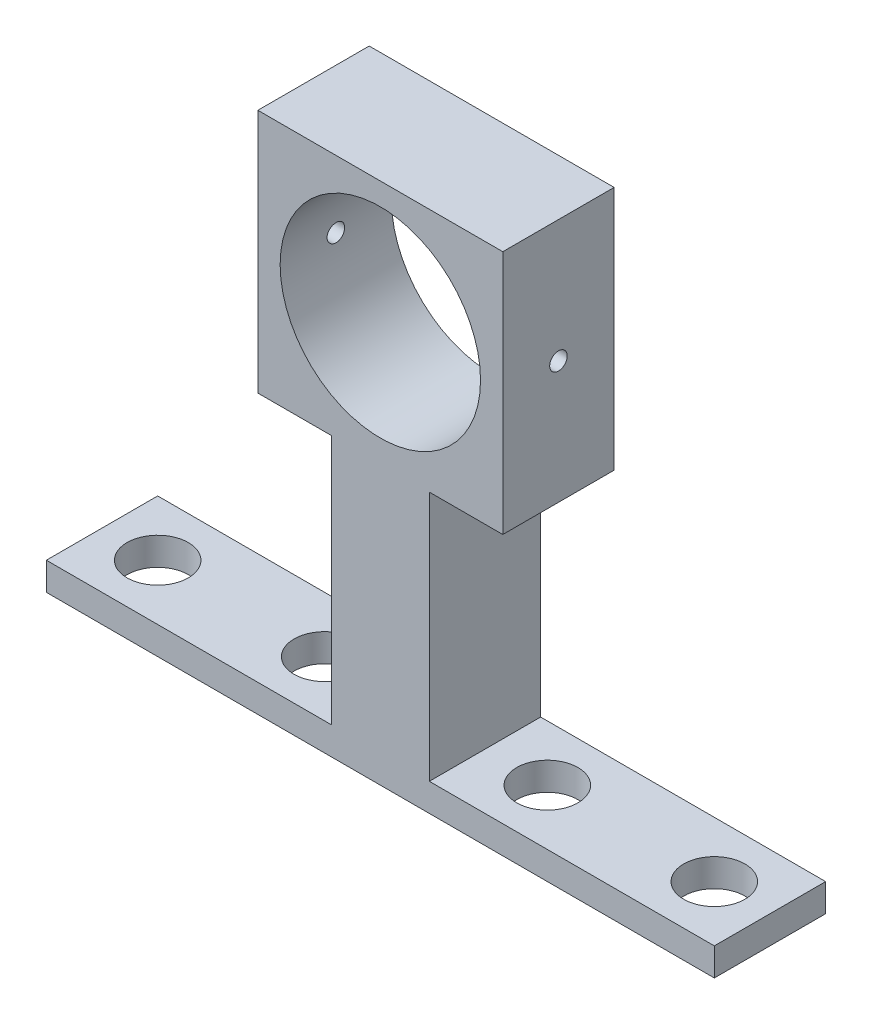
SolidWorks part; units mm, degrees
ref_plane "Front Plane" through (0, 0, 0) normal (0, 0, 1) x (1, 0, 0)
ref_plane "Top Plane" through (0, 0, 0) normal (0, 1, 0) x (1, 0, 0)
ref_plane "Right Plane" through (0, 0, 0) normal (1, 0, 0) x (0, 0, -1)
sketch "Sketch1" plane through (0, 0, 0) normal (0, 0, 1) x (1, 0, 0)
  line L0 (-38.1, 0) -> (38.1, 0)
  line L1 (38.1, 0) -> (38.1, 3.175)
  line L2 (38.1, 3.175) -> (5.588, 3.175)
  line L3 (5.588, 3.175) -> (5.588, 31.75)
  line L4 (5.588, 31.75) -> (13.97, 31.75)
  line L5 (13.97, 31.75) -> (13.97, 59.69)
  line L6 (13.97, 59.69) -> (-13.97, 59.69)
  line L7 (0, 59.69) -> (0, 0) construction
  line L8 (-38.1, 0) -> (-38.1, 3.175)
  line L9 (-38.1, 3.175) -> (-5.588, 3.175)
  line L10 (-5.588, 3.175) -> (-5.588, 31.75)
  line L11 (-5.588, 31.75) -> (-13.97, 31.75)
  line L12 (-13.97, 31.75) -> (-13.97, 59.69)
  circle A0 centre (0, 45.72) radius 11.43
  point P10 (13.97, 45.72)
  dimension "D5" = 11.43
  dimension "D1" = 38.1
  dimension "D2" = 3.175
  dimension "D3" = 31.75
  dimension "D4" = 27.94
  dimension "D6" = 5.588
  dimension "D7" = 13.97
extrude "Boss-Extrude1" add sketch "Sketch1" along normal mid plane 12.7
sketch "Sketch2" plane through (0, 3.175, 0) normal (0, 1, 0) x (1, 0, 0)
  circle A0 centre (-31.75, 0) radius 3.4925
  circle A1 centre (31.75, 0) radius 3.4925
  circle A2 centre (-12.7, 0) radius 3.4925
  circle A3 centre (12.7, 0) radius 3.4925
  dimension "D1" = 6.985
  dimension "D4" = 63.5
  dimension "D2" = 31.75
  dimension "D5" = 12.7
  dimension "D3" = 2
  dimension "D6" = 2
extrude "Cut-Extrude1" cut sketch "Sketch2" against normal through all
sketch "Sketch3" plane through (13.97, 0, 0) normal (1, 0, 0) x (0, 0, -1)
  line L0 (6.35, 31.75) -> (6.35, 59.69) construction
  circle A0 centre (0, 45.72) radius 1
  point P2 (0, 0)
  point P6 (6.35, 45.72)
  dimension "D1" = 2
extrude "Cut-Extrude2" cut sketch "Sketch3" against normal through all
